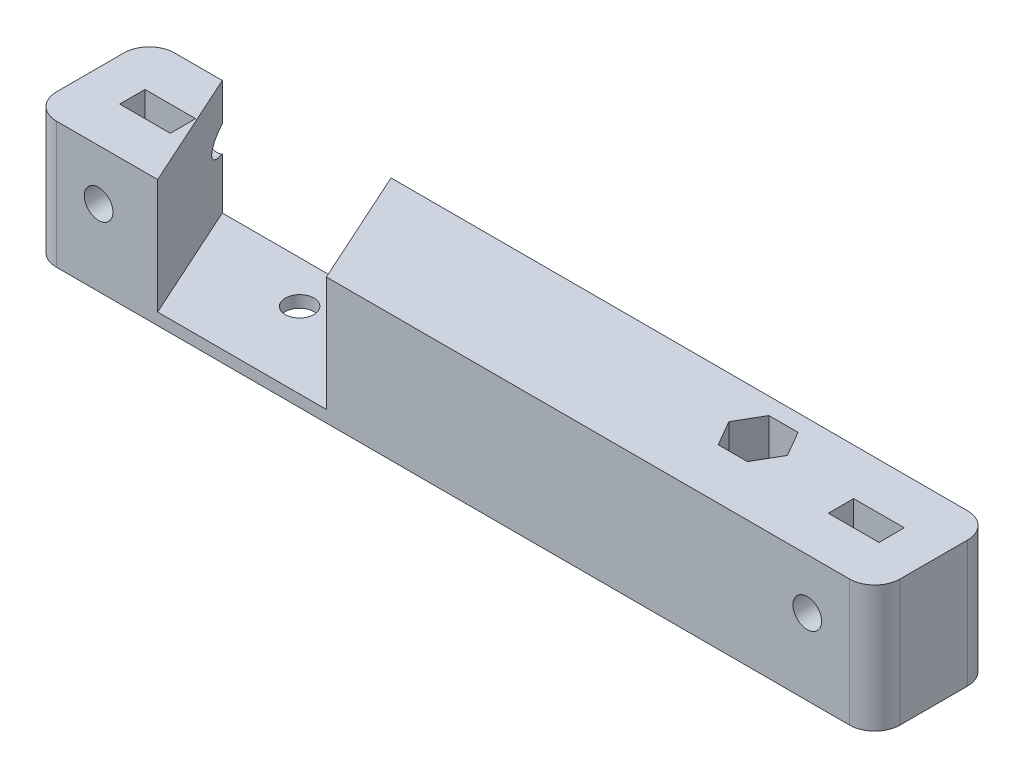
SolidWorks part; units mm, degrees
ref_plane "Front Plane" through (0, 0, 0) normal (0, 0, 1) x (1, 0, 0)
ref_plane "Top Plane" through (0, 0, 0) normal (0, 1, 0) x (1, 0, 0)
ref_plane "Right Plane" through (0, 0, 0) normal (1, 0, 0) x (0, 0, -1)
sketch "Sketch1" plane through (0, 0, 0) normal (0, 1, 0) x (1, 0, 0)
  line L1 (-50, 7) -> (50, 7)
  line L2 (-50, 7) -> (-50, -7)
  line L3 (-50, -7) -> (50, -7)
  line L4 (50, 7) -> (50, -7)
  line L5 (-50, 7) -> (50, -7) construction
  line L6 (-50, -7) -> (50, 7) construction
  circle A0 centre (-27.175, 2) radius 1.7
  circle A1 centre (27.175, 2) radius 1.7
  point P0 (0, 0)
  dimension "D3" = 5
  dimension "D7" = 3.4
  dimension "D8" = 3.4
  dimension "D1" = 14
  dimension "D2" = 100
  dimension "D4" = 5
  dimension "D5" = 27.175
  dimension "D6" = 27.175
extrude "Boss-Extrude1" add sketch "Sketch1" along normal blind 15
sketch "Sketch3" plane through (0, 0, 7) normal (0, 0, 1) x (1, 0, 0)
  line L1 (-50, 15) -> (-50, 0) construction
  line L2 (50, 15) -> (50, 0) construction
  line L3 (-50, 15) -> (50, 15) construction
  circle A0 centre (-42, 9) radius 1.7
  circle A1 centre (42, 9) radius 1.7
  dimension "D5" = 3.4
  dimension "D6" = 3.4
  dimension "D1" = 6
  dimension "D2" = 8
  dimension "D3" = 8
  dimension "D4" = 6
extrude "Cut-Extrude2" cut sketch "Sketch3" against normal through all
sketch "Sketch4" plane through (0, 0, 7) normal (0, 0, 1) x (1, 0, 0)
  line L0 (-45, 10.7321) -> (-45, 16.4519)
  line L2 (-45, 10.7321) -> (-45, 7.2679)
  line L3 (-45, 7.2679) -> (-42, 5.5359)
  line L4 (-42, 5.5359) -> (-39, 7.2679)
  line L5 (-39, 7.2679) -> (-39, 10.7321)
  line L7 (-45, 16.4519) -> (-39, 16.4519)
  line L8 (-39, 16.4519) -> (-39, 10.7321)
  line L9 (0, -7.7) -> (0, 7.7) construction
  line L10 (-39, 10.7321) -> (-40.5, 11.5981) [skipped]
  line L11 (-43.5, 11.5981) -> (-45, 10.7321) [skipped]
  line L12 (39, 16.4519) -> (39, 10.7321)
  line L13 (45, 16.4519) -> (39, 16.4519)
  line L14 (39, 7.2679) -> (39, 10.7321)
  line L15 (42, 5.5359) -> (39, 7.2679)
  line L16 (45, 7.2679) -> (42, 5.5359)
  line L17 (45, 10.7321) -> (45, 7.2679)
  line L18 (45, 10.7321) -> (45, 16.4519)
  arc A0 (-45, 9) -> (-39, 9) centre (-42, 9) ccw construction
  arc A1 (45, 9) -> (39, 9) centre (42, 9) cw construction
  dimension "D1" = 6
extrude "Cut-Extrude3" cut sketch "Sketch4" against normal mid plane 3 from surface at -7 starting at plane "Front Plane"
sketch "Sketch5" plane through (0, 15, 0) normal (0, 1, 0) x (1, 0, 0)
  line L7 (25.4429, -1) -> (23.7109, 2)
  line L8 (28.9071, -1) -> (25.4429, -1)
  line L9 (30.6391, 2) -> (28.9071, -1)
  line L10 (28.9071, 5) -> (30.6391, 2)
  line L11 (25.4429, 5) -> (28.9071, 5)
  line L12 (23.7109, 2) -> (25.4429, 5)
  circle A1 centre (27.175, 2) radius 3 construction
extrude "Cut-Extrude4" cut sketch "Sketch5" against normal blind 6
fillet "Fillet4" radius 3 4 edges at (50, 7.5, -7) (50, 7.5, 7) (-50, 7.5, 7) (-50, 7.5, -7)
sketch "Sketch6" plane through (0, 15, 0) normal (0, 1, 0) x (1, 0, 0)
  line L0 (-35, 11.2689) -> (-35, -11.717) construction
  line L1 (-50, 4) -> (-50, -4) construction
  line L2 (-35, -7) -> (-41.3381, 7)
  line L3 (-47, -7) -> (47, -7) construction
  line L4 (47, 7) -> (-47, 7) construction
  line L5 (-21.3381, 7) -> (-15, -7)
  line L6 (-41.3381, 7) -> (-21.3381, 7)
  line L7 (-15, -7) -> (-35, -7)
  dimension "D1" = 15
  dimension "D2" = 20
  dimension "D3" = 20
extrude "Cut-Extrude5" cut sketch "Sketch6" against normal blind 13.6
